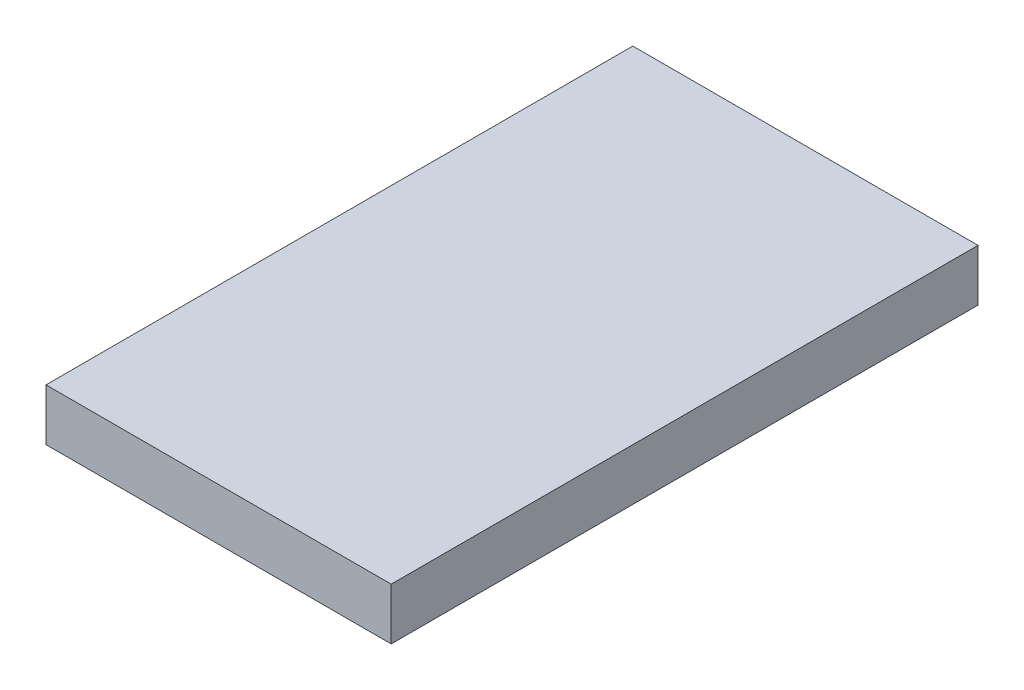
SolidWorks part; units mm, degrees
ref_plane "Front Plane" through (0, 0, 0) normal (0, 0, 1) x (1, 0, 0)
ref_plane "Top Plane" through (0, 0, 0) normal (0, 1, 0) x (1, 0, 0)
ref_plane "Right Plane" through (0, 0, 0) normal (1, 0, 0) x (0, 0, -1)
sketch "Sketch1" plane through (0, 0, 0) normal (0, 1, 0) x (1, 0, 0)
  line L1 (-10, 17) -> (10, 17)
  line L2 (-10, 17) -> (-10, -17)
  line L3 (-10, -17) -> (10, -17)
  line L4 (10, 17) -> (10, -17)
  line L5 (-10, 17) -> (10, -17) construction
  line L6 (-10, -17) -> (10, 17) construction
  point P0 (0, 0)
  dimension "D1" = 34
  dimension "D2" = 20
extrude "Boss-Extrude1" add sketch "Sketch1" along normal blind 3
